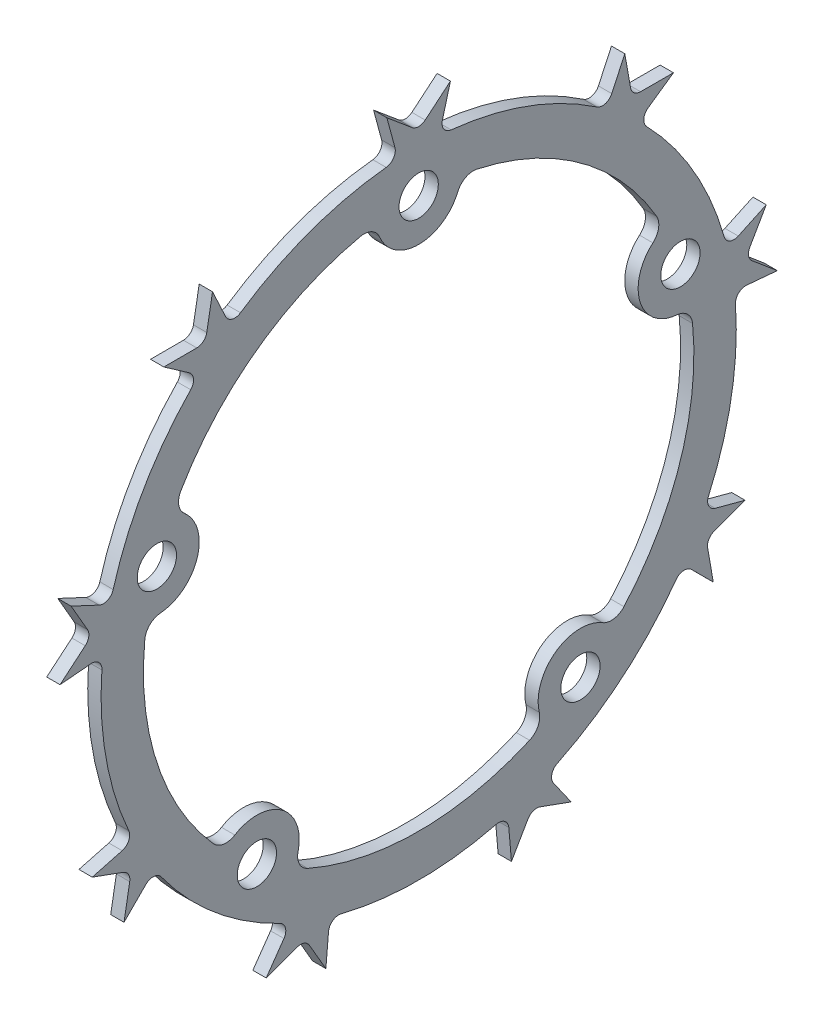
SolidWorks part; units mm, degrees
ref_plane "Front Plane" through (0, 0, 0) normal (0, 0, 1) x (1, 0, 0)
ref_plane "Top Plane" through (0, 0, 0) normal (0, 1, 0) x (1, 0, 0)
ref_plane "Right Plane" through (0, 0, 0) normal (1, 0, 0) x (0, 0, -1)
sketch "Sketch1" plane through (0, 0, 0) normal (1, 0, 0) x (0, 0, -1)
  circle A0 centre (0, 0) radius 25.4 construction
  circle A1 centre (0, 0) radius 23.8125
  circle A2 centre (0, 0) radius 20.6375
  dimension "D1" = 50.8
  dimension "D2" = 1.5875
  dimension "D3" = 3.175
extrude "Boss-Extrude1" add sketch "Sketch1" along normal blind 1
sketch "Sketch2" plane through (1, 0, 0) normal (1, 0, 0) x (0, 0, -1)
  line L0 (0, 23.8125) -> (0, 33.1916) construction
  line L1 (1.5417, 23.7625) -> (2.3813, 26.8822)
  line L2 (2.3813, 26.8822) -> (0, 24.8885)
  line L3 (0, 24.8885) -> (-2.3813, 26.8822)
  line L4 (-2.3813, 26.8822) -> (-1.5417, 23.7625)
  line L5 (-2.3813, 26.8822) -> (2.3813, 26.8822) construction
  line L6 (0, 0) -> (-2.3813, 26.8822) construction
  circle A0 centre (0, 0) radius 23.8125 construction
  arc A1 (-1.5417, 23.7625) -> (1.5417, 23.7625) centre (0, 0) cw
  circle A2 centre (0, 0) radius 26.9875 construction
  dimension "D1" = 3.175
  dimension "D2" = 10
  dimension "D3" = 4.7625
  dimension "D4" = 35
extrude "Boss-Extrude2" add sketch "Sketch2" against normal up to surface (1 mm away) up to face at (0, 0, -23.8125)
fillet "Fillet1" radius 0.762 3 edges at (0.5, 23.7625, -1.5417) (0.5, 24.8885, 0) (0.5, 23.7625, 1.5417)
pattern_circular "CirPattern1" count 9 over 360 about axis through (0, 0, 0) along (1, 0, 0) of "Fillet1", "Boss-Extrude2"
sketch "Sketch3" plane through (1, 0, 0) normal (1, 0, 0) x (0, 0, -1)
  line L0 (0, 0) -> (0, 20.6375) construction
  circle A0 centre (0, 20.6375) radius 1.4605 construction
  circle A1 centre (0, 20.6375) radius 3.175
  circle A2 centre (0, 0) radius 20.6375 construction
  dimension "D1" = 2.921
  dimension "D2" = 6.35
extrude "Boss-Extrude3" add sketch "Sketch3" against normal up to surface (1 mm away) up to face at (0, 0, 0)
fillet "Fillet2" radius 1.27 2 edges at (0.5, 20.3933, -3.1656) (0.5, 20.3933, 3.1656)
hole_wizard "#4 Clearance Hole1" positions "Sketch4" profile "Sketch5" hole size "#4" standard "ANSI Inch" end condition up to next
sketch "Sketch4" plane through (1, 0, 0) normal (1, 0, 0) x (0, 0, -1)
  point P0 (0, 20.6375)
sketch "Sketch5" plane through (1, 20.6375, 0) normal (0, 1, 0) x (0, 0, -1)
  line L0 (0, 0) -> (0, 1)
  line L1 (0, 1) -> (1.4732, 1)
  line L2 (1.4732, 1) -> (1.4732, 0)
  line L5 (1.4732, 0) -> (0, 0)
  line L11 (0, -6.35) -> (0, 107.95) construction
  dimension "Thru Hole Dia." = 2.9464
  dimension "Thru Hole Depth" = 1
pattern_circular "CirPattern2" count 5 over 360 about axis through (0, 0, 0) along (1, 0, 0) of "#4 Clearance Hole1", "Fillet2", "Boss-Extrude3"
equation "\"D1@Boss-Extrude1\"=1mm"
